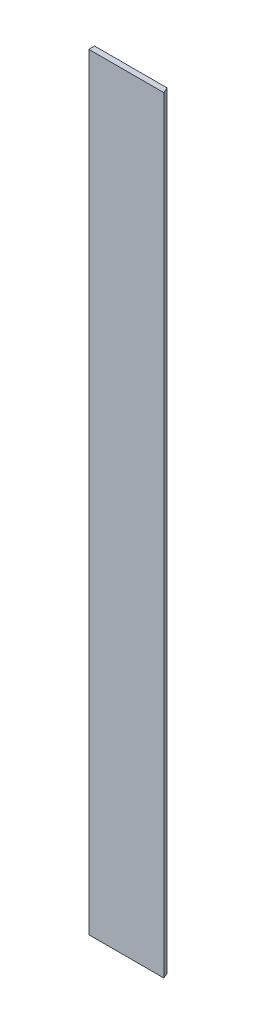
SolidWorks part; units mm, degrees
ref_plane "Спереди" through (0, 0, 0) normal (0, 0, 1) x (1, 0, 0)
ref_plane "Сверху" through (0, 0, 0) normal (0, 1, 0) x (1, 0, 0)
ref_plane "Справа" through (0, 0, 0) normal (1, 0, 0) x (0, 0, -1)
sketch "Эскиз1" plane through (0, 0, 0) normal (0, 1, 0) x (1, 0, 0)
  line L1 (0, -1) -> (50.4852, -1)
  line L2 (0, -1) -> (0, -5)
  line L3 (0, -5) -> (52.1029, -5)
  line L4 (50.4852, -1) -> (52.1029, -5)
  dimension "D1" = 4
extrude "Вытянуть1" add sketch "Эскиз1" along normal up to surface (533.2137 mm away)
